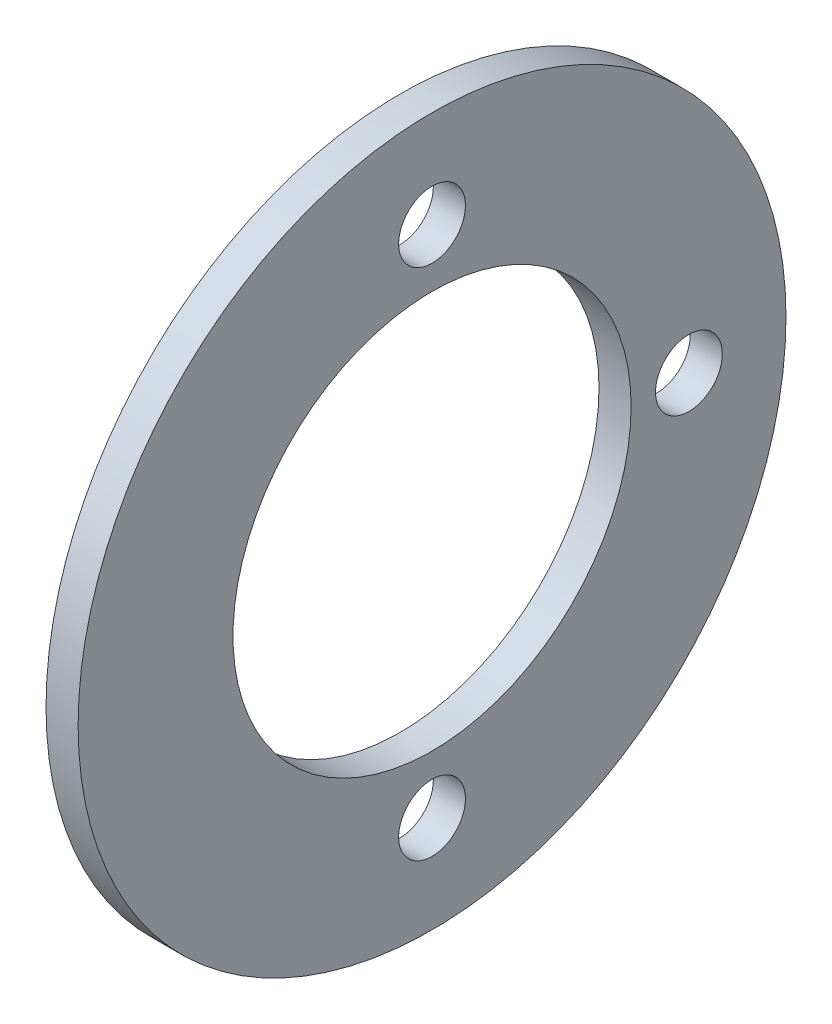
SolidWorks part; units mm, degrees
ref_plane "Front Plane" through (0, 0, 0) normal (0, 0, 1) x (1, 0, 0)
ref_plane "Top Plane" through (0, 0, 0) normal (0, 1, 0) x (1, 0, 0)
ref_plane "Right Plane" through (0, 0, 0) normal (1, 0, 0) x (0, 0, -1)
sketch "Sketch1" plane through (0, 0, 0) normal (1, 0, 0) x (0, 0, -1)
  circle A0 centre (0, 0) radius 19.685
  circle A1 centre (0, 0) radius 35
  circle A2 centre (0, 25.4) radius 3.302
  circle A3 centre (25.4, 0) radius 3.302
  circle A4 centre (0, -25.4) radius 3.302
  circle A5 centre (-25.4, 0) radius 3.302 [skipped]
  dimension "D1" = 70
  dimension "D3" = 6.604
  dimension "D5" = 39.37
  dimension "D2" = 25.4
  dimension "D4" = 4
extrude "Boss-Extrude1" add sketch "Sketch1" along normal blind 3.175
